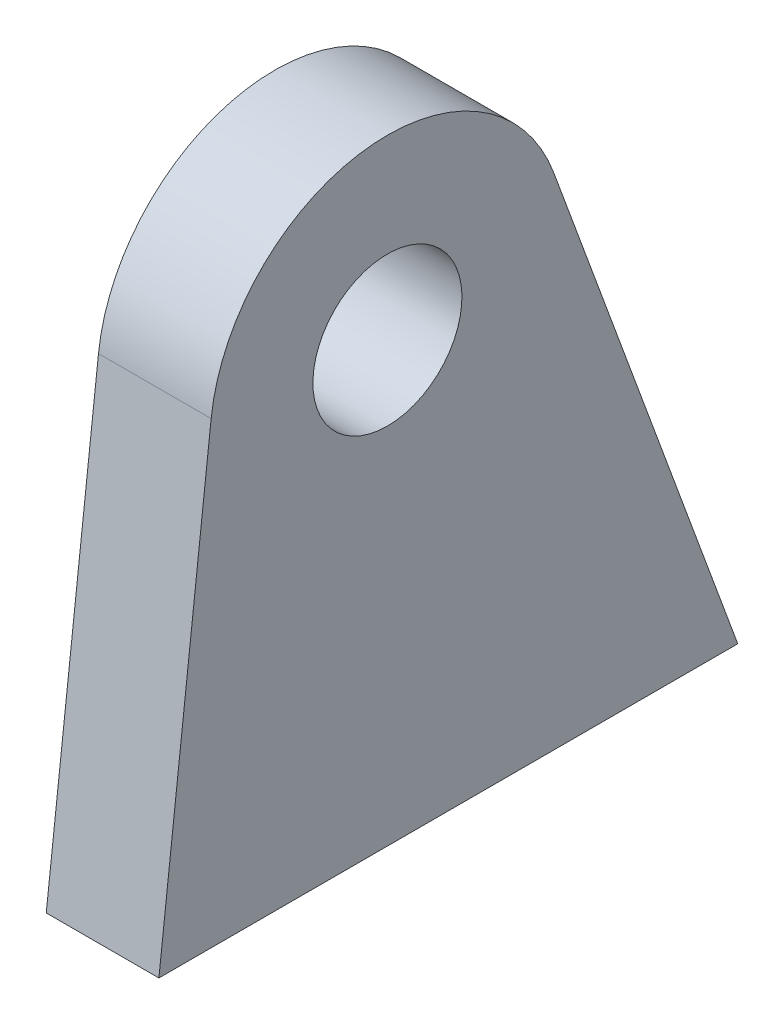
SolidWorks part; units mm, degrees
material "AISI 4130 Steel, normalized at 870C"
ref_plane "Front Plane" through (0, 0, 0) normal (0, 0, 1) x (1, 0, 0)
ref_plane "Top Plane" through (0, 0, 0) normal (0, 1, 0) x (1, 0, 0)
ref_plane "Right Plane" through (0, 0, 0) normal (1, 0, 0) x (0, 0, -1)
sketch "Sketch1" plane through (-81.7, 0, 0) normal (-1, 0, 0) x (0, 0, 1)
  line L0 (-916.7136, 360.6774) -> (-927.0751, 332.5236)
  line L1 (-927.0751, 332.5236) -> (-894.4484, 332.5236)
  line L2 (-894.4484, 332.5236) -> (-897.3933, 358.3563)
  circle A0 centre (-907.329, 357.2236) radius 4.2
  arc A1 (-897.3933, 358.3563) -> (-916.7136, 360.6774) centre (-907.329, 357.2236) ccw
  dimension "D1" = 8.4
  dimension "D3" = 10
  dimension "D2" = 24.7
  dimension "D4" = 26
  dimension "D5" = 30
extrude "Boss-Extrude1" add sketch "Sketch1" along normal blind 6.35
